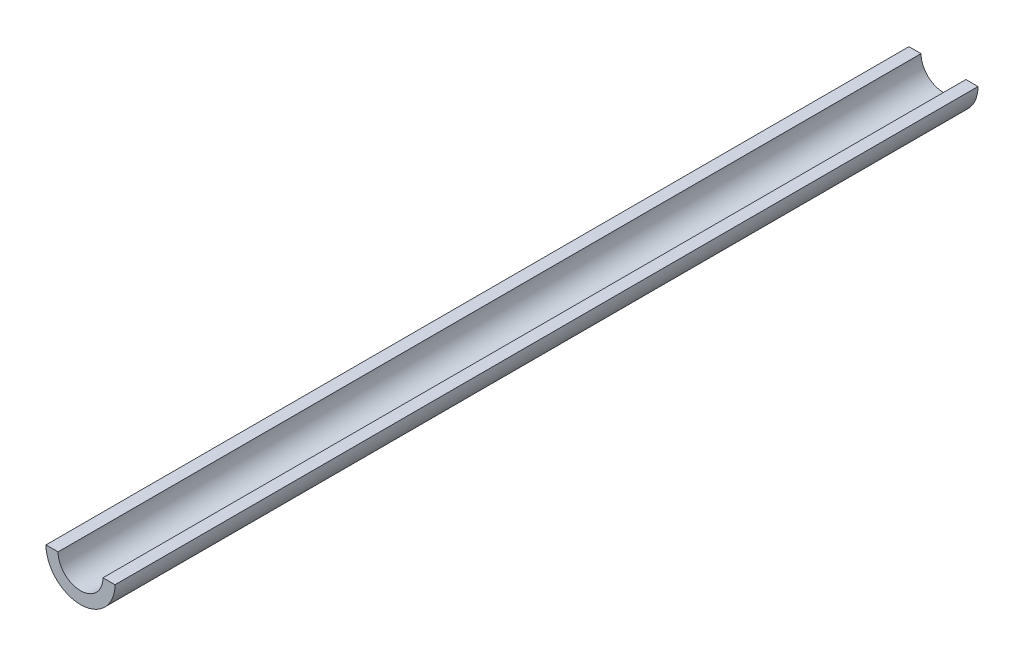
SolidWorks part; units mm, degrees
ref_plane "前视基准面" through (0, 0, 0) normal (0, 0, 1) x (1, 0, 0)
ref_plane "上视基准面" through (0, 0, 0) normal (0, 1, 0) x (1, 0, 0)
ref_plane "右视基准面" through (0, 0, 0) normal (1, 0, 0) x (0, 0, -1)
sketch "草图1" plane through (0, 0, 0) normal (0, 0, 1) x (1, 0, 0)
  line L0 (0, 8.1398) -> (0, -8.1398) construction
  line L1 (-8.1398, 0) -> (8.1398, 0) construction
  line L2 (6.5, 0) -> (10, 0)
  line L3 (-6.5, 0) -> (-10, 0)
  arc A0 (-6.5, 0) -> (6.5, 0) centre (0, 0) ccw
  arc A1 (-10, 0) -> (10, 0) centre (0, 0) ccw
  circle A2 centre (0, 0) radius 5 construction
  dimension "D1" = 10
  dimension "D2" = 6.5
  dimension "D3" = 10
  dimension "D4" = 20
extrude "凸台-拉伸1" add sketch "草图1" along normal mid plane 250
